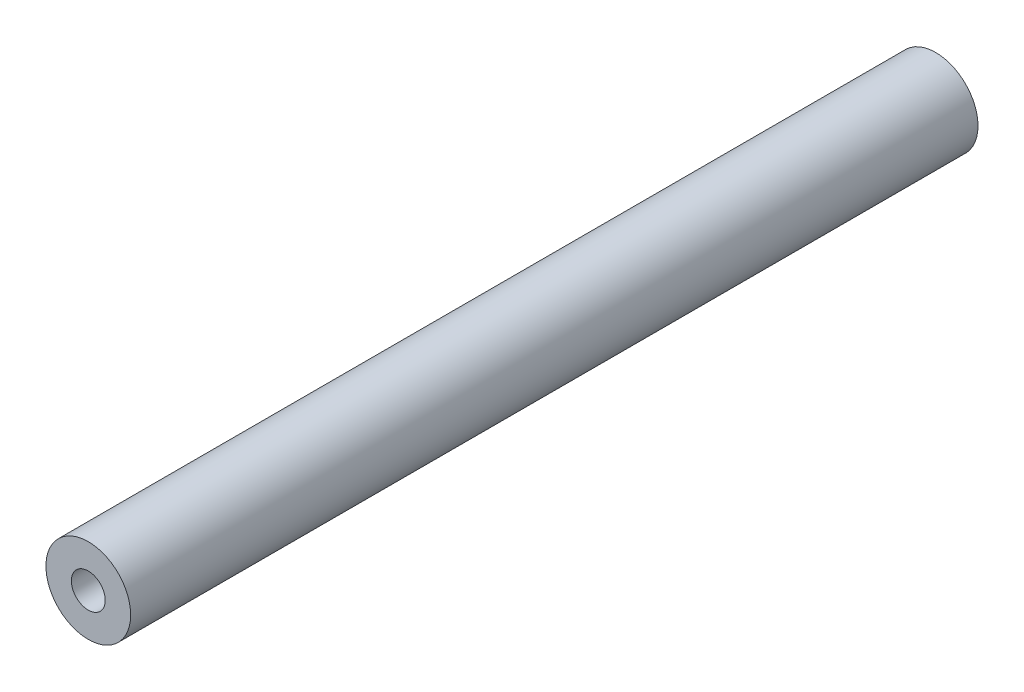
SolidWorks part; units mm, degrees
material "Zoltek Panex 33"
ref_plane "Front Plane" through (0, 0, 0) normal (0, 0, 1) x (1, 0, 0)
ref_plane "Top Plane" through (0, 0, 0) normal (0, 1, 0) x (1, 0, 0)
ref_plane "Right Plane" through (0, 0, 0) normal (1, 0, 0) x (0, 0, -1)
sketch "草圖1" plane through (0, 0, 0) normal (0, 0, 1) x (1, 0, 0)
  circle A0 centre (0, 0) radius 3
  dimension "D1" = 6
extrude "伸長-薄件1" add sketch "草圖1" along normal blind 60 thin thin type one direction reverse wall 1.8
